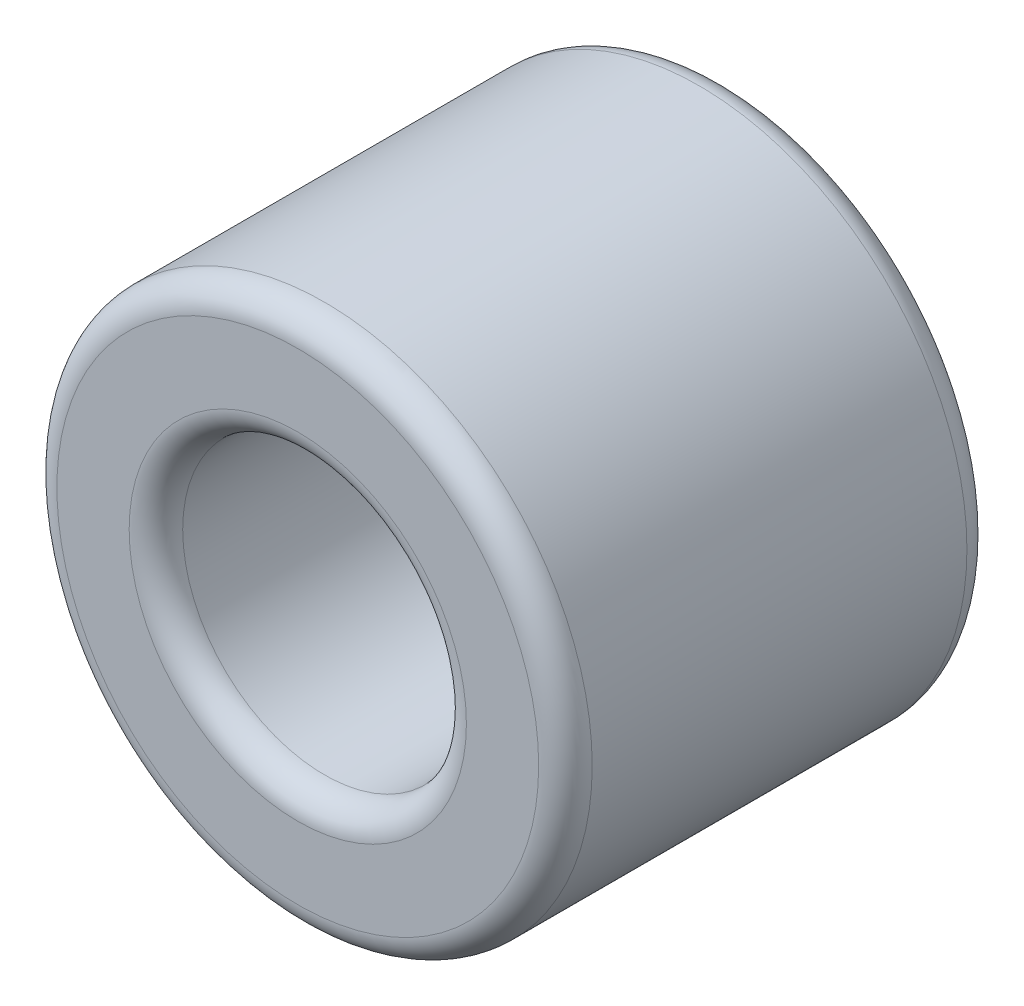
SolidWorks part; units mm, degrees
ref_plane "Front Plane" through (0, 0, 0) normal (0, 0, 1) x (1, 0, 0)
ref_plane "Top Plane" through (0, 0, 0) normal (0, 1, 0) x (1, 0, 0)
ref_plane "Right Plane" through (0, 0, 0) normal (1, 0, 0) x (0, 0, -1)
sketch "Sketch1" plane through (0, 0, 0) normal (0, 0, 1) x (1, 0, 0)
  circle A0 centre (0, 0) radius 2.65
  circle A1 centre (0, 0) radius 5
  dimension "D1" = 5.3
  dimension "D2" = 10
extrude "spacer" add sketch "Sketch1" along normal blind 8
fillet "Fillet1" radius 0.5 4 edges at (2.65, 0, 0) (2.65, 0, 8) (5, 0, 0) (5, 0, 8)
